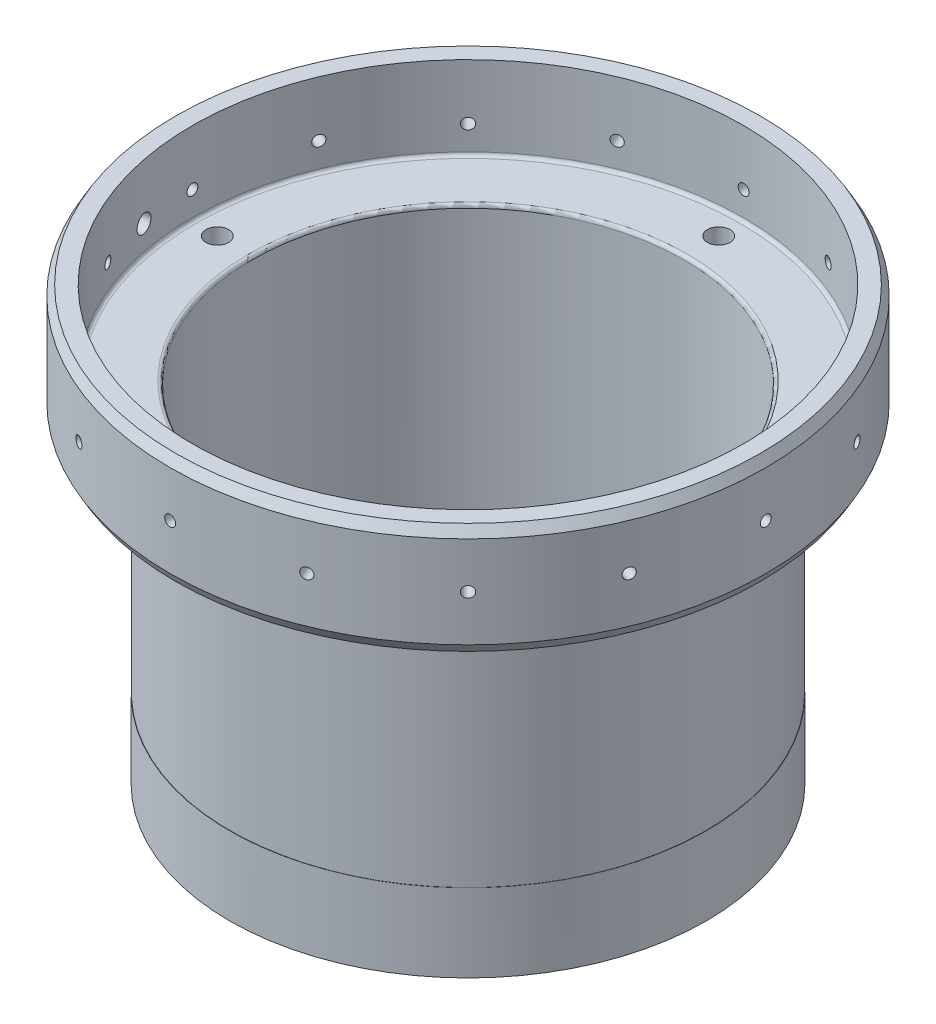
SolidWorks part; units mm, degrees
material "6061-T6 (SS)"
ref_plane "Front Plane" through (0, 0, 0) normal (0, 0, 1) x (1, 0, 0)
ref_plane "Top Plane" through (0, 0, 0) normal (0, 1, 0) x (1, 0, 0)
ref_plane "Right Plane" through (0, 0, 0) normal (1, 0, 0) x (0, 0, -1)
sketch "Sketch1" plane through (0, 0, 0) normal (0, 0, 1) x (1, 0, 0)
  line L0 (0, 0) -> (0, 9.1321) construction
  line L1 (0, 0) -> (-63.119, 0) construction
  line L2 (-63.119, 0) -> (-68.199, 0)
  line L3 (-68.199, 0) -> (-68.199, -25.4)
  line L4 (-68.199, -25.4) -> (-54.6024, -25.4)
  line L5 (-54.6024, -25.4) -> (-54.6024, -33.909)
  line L6 (-54.5516, -99.6696) -> (-49.4665, -99.6696)
  line L7 (-49.4665, -99.6696) -> (-49.4665, -19.05)
  line L8 (-49.4665, -19.05) -> (-63.119, -19.05)
  line L9 (-63.119, -19.05) -> (-63.119, 0)
  line L10 (-54.6024, -33.909) -> (-54.4881, -33.909)
  line L11 (-54.4881, -33.909) -> (-54.4881, -81.026)
  line L12 (-54.4881, -81.026) -> (-54.5516, -81.026)
  line L13 (-54.5516, -81.026) -> (-54.5516, -99.6696)
  dimension "D1" = 5.08
  dimension "D2" = 68.199
  dimension "D3" = 25.4
  dimension "D4" = 6.35
  dimension "D5" = 74.2696
  dimension "D6" = 49.4665
  dimension "D7" = 54.5516
  dimension "D8" = 8.509
  dimension "D9" = 47.117
  dimension "D10" = 54.6024
  dimension "D11" = 54.4881
revolve "Revolve6" add sketch "Sketch1" angle 360 about L0
sketch "Sketch2" plane through (0, 0, 0) normal (0, 1, 0) x (1, 0, 0)
  line L0 (0, 0) -> (-68.199, 0) construction
  line L1 (0, 0) -> (-66.8886, -13.305) construction
  circle A0 centre (0, 0) radius 68.199 construction
  dimension "D1" = 11.25
ref_plane "Plane1" through (-68.199, 0, 0) normal (-1, 0, 0) x (0, 0, 1)
sketch "Sketch3" plane through (-68.199, 0, 0) normal (-1, 0, 0) x (0, 0, 1)
  line L0 (0, 0) -> (0, -12.7) construction
  dimension "D1" = 12.7
hole_wizard "Tap Drill for M3x0.5 Tap1" positions "Sketch5" profile "Sketch4" hole size "M3x0.5" standard "Ansi Metric"
sketch "Sketch5" plane through (-68.199, 0, 0) normal (-1, 0, 0) x (0, 0, 1)
  point P1 (0, -12.7)
sketch "Sketch4" plane through (-68.199, -12.7, 0) normal (0, 1, 0) x (0, 0, 1)
  line L0 (0, 0) -> (0, 10.9111)
  line L1 (0, 10.9111) -> (1.25, 10.16)
  line L2 (1.25, 10.16) -> (1.25, 0)
  line L5 (1.25, 0) -> (0, 0)
  line L10 (0, 10.9111) -> (-1.25, 10.16) construction
  line L11 (0, -6.35) -> (0, 107.95) construction
  dimension "Hole Dia." = 2.5
  dimension "Hole Depth" = 10.16
  dimension "Drill Angle" = 118
pattern_circular "CirPattern1" count 16 over 360 about axis through (0, 0, 0) along (0, -1, 0) of "Tap Drill for M3x0.5 Tap1"
ref_plane "Plane2" through (-66.8886, 0, 13.305) normal (-0.9808, 0, 0.1951) x (0.1951, 0, 0.9808)
sketch "Sketch6" plane through (-66.8886, 0, 13.305) normal (-0.9808, 0, 0.1951) x (0.1951, 0, 0.9808)
  line L0 (0, 0) -> (0, -12.7) construction
  dimension "D1" = 12.7
hole_wizard "Tap Drill for #10-32 Tap1" positions "Sketch8" profile "Sketch7" hole size "#10-32" standard "Ansi Inch"
sketch "Sketch8" plane through (-66.8886, 0, 13.305) normal (-0.9808, 0, 0.1951) x (0.1951, 0, 0.9808)
  point P1 (0, -12.7)
sketch "Sketch7" plane through (-66.8886, -12.7, 13.305) normal (0, 1, 0) x (0.1951, 0, 0.9808)
  line L0 (0, 0) -> (0, 11.3733)
  line L1 (0, 11.3733) -> (2.0193, 10.16)
  line L2 (2.0193, 10.16) -> (2.0193, 0)
  line L5 (2.0193, 0) -> (0, 0)
  line L10 (0, 11.3733) -> (-2.0193, 10.16) construction
  line L11 (0, -6.35) -> (0, 107.95) construction
  dimension "Hole Dia." = 4.0386
  dimension "Hole Depth" = 10.16
  dimension "Drill Angle" = 118
sketch "Sketch9" plane through (0, -99.6696, 0) normal (0, -1, 0) x (1, 0, 0)
  line L0 (54.5516, 0) -> (49.4665, 0) construction
  circle A2 centre (0, 0) radius 49.4665 construction
  circle A3 centre (0, 0) radius 54.5516 construction
  point P9 (52.009, 0)
  dimension "D1" = 52.009
hole_wizard "Tap Drill for #4-40 Tap1" positions "3DSketch1" profile "Sketch10" hole size "#4-40" standard "Ansi Inch"
sketch3d "3DSketch1"
  point P0 (52.009, -99.6696, 0)
sketch "Sketch10" plane through (52.009, -99.6696, 0) normal (1, 0, 0) x (0, 0, -1)
  line L0 (0, 0) -> (0, 18.4592)
  line L1 (0, 18.4592) -> (1.1303, 17.78)
  line L2 (1.1303, 17.78) -> (1.1303, 0)
  line L5 (1.1303, 0) -> (0, 0)
  line L10 (0, 18.4592) -> (-1.1303, 17.78) construction
  line L11 (0, -6.35) -> (0, 107.95) construction
  dimension "Hole Dia." = 2.2606
  dimension "Hole Depth" = 17.78
  dimension "Drill Angle" = 118
pattern_circular "CirPattern2" count 16 over 360 about axis through (0, 0, 0) along (0, 1, 0) of "Tap Drill for #4-40 Tap1"
sketch "Sketch12" plane through (0, -25.4, 0) normal (0, -1, 0) x (1, 0, 0)
  line L0 (0, 54.6024) -> (0, 57.3964) construction
  circle A0 centre (0, 0) radius 54.6024 construction
  circle A1 centre (0, 0) radius 54.6024 construction
  dimension "D1" = 2.794
hole_wizard "13/64 (0.20313) Diameter Hole1" positions "3DSketch2" profile "Sketch14" hole size "13/64" standard "Ansi Inch" end condition through all
sketch3d "3DSketch2"
  point P0 (0, -25.4, 57.3964)
sketch "Sketch14" plane through (0, -25.4, 57.3964) normal (1, 0, 0) x (0, 0, -1)
  line L0 (0, 0) -> (0, 25.4)
  line L1 (0, 25.4) -> (2.5798, 25.4)
  line L2 (2.5798, 25.4) -> (2.5798, 0)
  line L5 (2.5798, 0) -> (0, 0)
  line L11 (0, -6.35) -> (0, 107.95) construction
  dimension "Thru Hole Dia." = 5.1595
  dimension "Thru Hole Depth" = 25.4
pattern_circular "CirPattern3" count 4 over 360 about axis through (0, 0, 0) along (0, 1, 0) of "13/64 (0.20313) Diameter Hole1"
chamfer "Chamfer2" distance 1.27 angle 60 2 edges at (0, -25.4, -68.199) (0, 0, -68.199)
chamfer "Chamfer4" distance 0.762 angle 60 1 edges at (0, -99.6696, -54.5516)
chamfer "Chamfer5" distance 0.762 angle 60 1 edges at (0, -99.6696, -49.4665)
fillet "Fillet1" radius 0.762 2 edges at (0, -19.05, -63.119) (0, -19.05, -49.4665)
